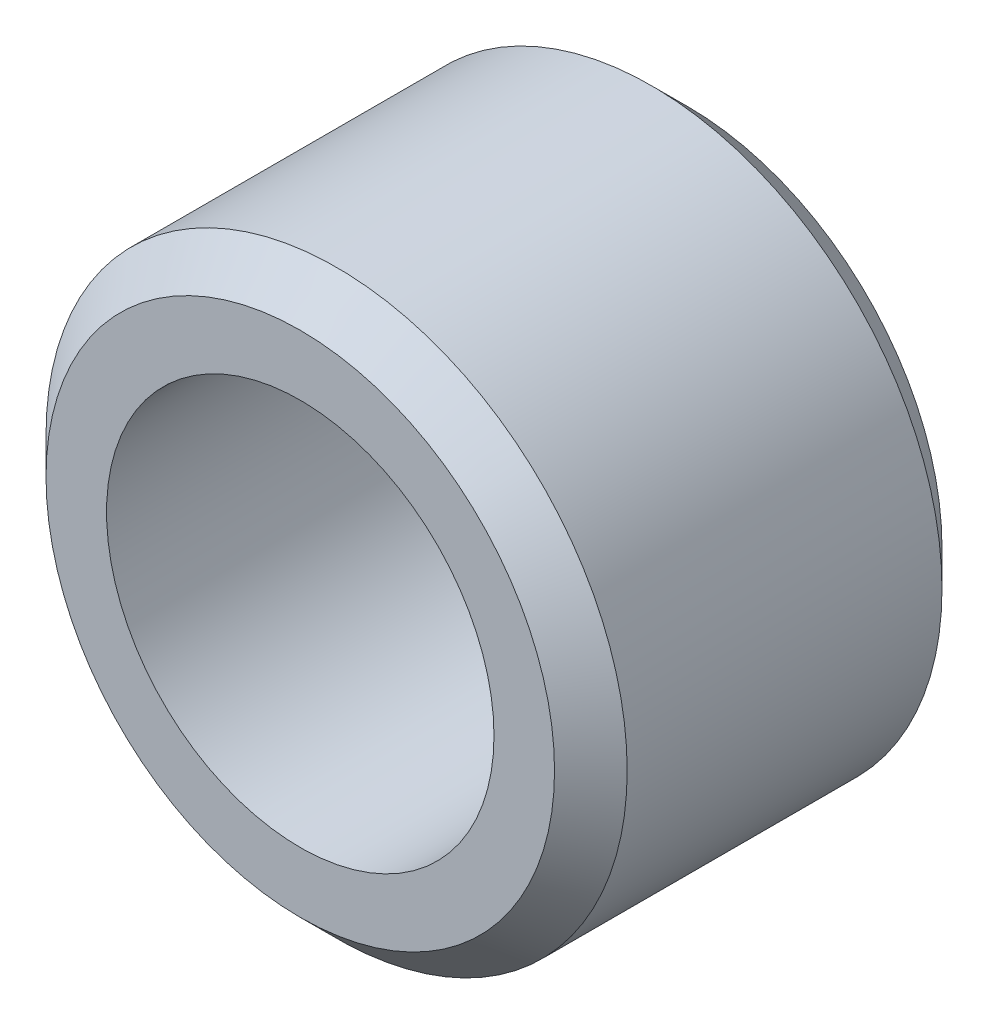
SolidWorks part; units mm, degrees
ref_plane "Front Plane" through (0, 0, 0) normal (0, 0, 1) x (1, 0, 0)
ref_plane "Top Plane" through (0, 0, 0) normal (0, 1, 0) x (1, 0, 0)
ref_plane "Right Plane" through (0, 0, 0) normal (1, 0, 0) x (0, 0, -1)
sketch "Sketch1" plane through (0, 0, 0) normal (1, 0, 0) x (0, 0, -1)
  line L0 (-3.175, 0) -> (3.175, 0) construction
  line L1 (3.175, 4.7625) -> (3.175, -4.7625) construction
  line L2 (-3.175, 4.7625) -> (-3.175, -4.7625) construction
  line L3 (3.175, 4.7625) -> (-3.175, 4.7625) construction
  line L4 (3.175, -4.7625) -> (-3.175, -4.7625) construction
  line L5 (-3.175, 3.175) -> (3.175, 3.175) construction
  line L6 (-3.175, -3.175) -> (3.175, -3.175) construction
  point P2 (0, 0)
  point P7 (-3.175, 0)
  point P8 (-3.175, -3.175)
  point P9 (3.175, 0)
  point P11 (-3.175, 3.175)
  dimension "OD" = 9.525
  dimension "ID" = 6.35
  dimension "Length" = 6.35
sketch "Sketch2" plane through (0, 0, 0) normal (0, 0, 1) x (1, 0, 0)
  line L0 (-4.7625, 0) -> (4.7625, 0) construction
  line L1 (0, -4.7625) -> (0, 4.7625) construction
  circle A0 centre (0, 0) radius 3.175 construction
  circle A1 centre (0, 0) radius 4.7625 construction
  point P16 (0, 0)
  dimension "ID" = 6.35
  dimension "OD" = 9.525
sketch "Sketch3" plane through (0, 0, 0) normal (1, 0, 0) x (0, 0, -1)
  line L0 (-3.175, 3.175) -> (3.175, 3.175)
  line L1 (3.175, 4.7625) -> (3.175, -4.7625) construction
  line L2 (3.175, 3.175) -> (3.175, 4.7625)
  line L5 (3.175, 4.7625) -> (-3.175, 4.7625)
  line L6 (-3.175, 4.7625) -> (-3.175, 3.175)
  line L7 (-3.175, 0) -> (3.175, 0) construction
revolve "Revolve1" add sketch "Sketch3" angle 360 about L7
chamfer "Chamfer1" distance 0.5953 angle 45 2 edges at (4.7625, 0, 3.175) (4.7625, 0, -3.175)
equation "\"D1@Chamfer1\"=((\"OD@Sketch1\"-\"ID@Sketch1\")/2)*.375"
